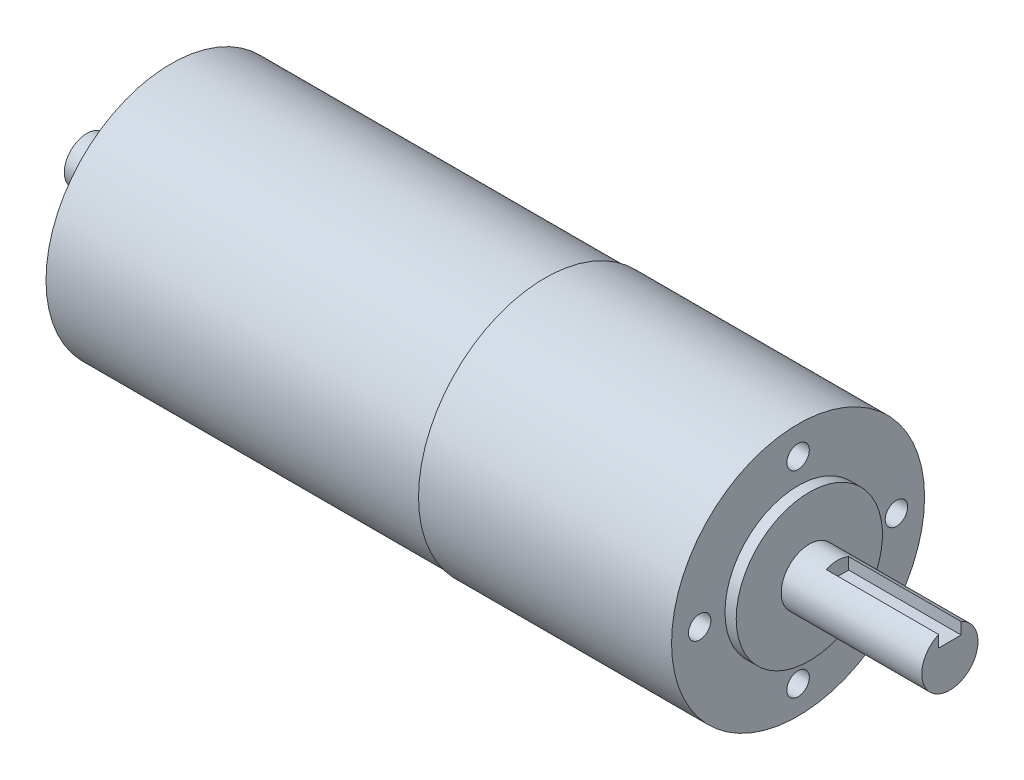
SolidWorks part; units mm, degrees
ref_plane "Front Plane" through (0, 0, 0) normal (0, 0, 1) x (1, 0, 0)
ref_plane "Top Plane" through (0, 0, 0) normal (0, 1, 0) x (1, 0, 0)
ref_plane "Right Plane" through (0, 0, 0) normal (1, 0, 0) x (0, 0, -1)
sketch "Sketch1" plane through (0, 0, 0) normal (1, 0, 0) x (0, 0, -1)
  circle A0 centre (0, 0) radius 5
  dimension "D1" = 10
extrude "Boss-Extrude1" add sketch "Sketch1" against normal blind 25
sketch "Sketch2" plane through (-25, 0, 0) normal (-1, 0, 0) x (0, 0, 1)
  circle A0 centre (0, 0) radius 13
  dimension "D1" = 26
extrude "Boss-Extrude2" add sketch "Sketch2" along normal blind 2
sketch "Sketch3" plane through (-27, 0, 0) normal (-1, 0, 0) x (0, 0, 1)
  circle A0 centre (0, 0) radius 22.5
  dimension "D1" = 45
extrude "Boss-Extrude3" add sketch "Sketch3" along normal blind 45
sketch "Sketch4" plane through (-72, 0, 0) normal (-1, 0, 0) x (0, 0, 1)
  circle A0 centre (0, 0) radius 22.25
  dimension "D1" = 44.5
extrude "Boss-Extrude4" add sketch "Sketch4" along normal blind 66.5
sketch "Sketch5" plane through (-138.5, 0, 0) normal (-1, 0, 0) x (0, 0, 1)
  circle A0 centre (0, 0) radius 10
  dimension "D1" = 20
extrude "Boss-Extrude5" add sketch "Sketch5" along normal blind 5
sketch "Sketch6" plane through (-143.5, 0, 0) normal (-1, 0, 0) x (0, 0, 1)
  circle A0 centre (0, 0) radius 4
  dimension "D1" = 8
extrude "Boss-Extrude6" add sketch "Sketch6" along normal blind 10
sketch "Sketch7" plane through (-27, 0, 0) normal (1, 0, 0) x (0, 0, -1)
  circle A0 centre (0, 17.5) radius 2
  circle A1 centre (0, 0) radius 17.5 construction
  circle A2 centre (17.5, 0) radius 2
  circle A3 centre (0, -17.5) radius 2
  circle A4 centre (-17.5, 0) radius 2
  dimension "D1" = 35
  dimension "D2" = 4
  dimension "D3" = 4
extrude "Cut-Extrude1" cut sketch "Sketch7" against normal blind 9
sketch "Sketch8" plane through (0, 0, 0) normal (1, 0, 0) x (0, 0, -1)
  line L1 (-2, 5) -> (2, 5)
  line L2 (-2, 5) -> (-2, 2.5)
  line L3 (-2, 2.5) -> (2, 2.5)
  line L4 (2, 5) -> (2, 2.5)
  line L5 (-2, 5) -> (2, 2.5) construction
  line L6 (-2, 2.5) -> (2, 5) construction
  circle A1 centre (0, 0) radius 5 construction
  point P0 (0, 3.75)
  dimension "D1" = 2.5
  dimension "D2" = 4
extrude "Cut-Extrude2" cut sketch "Sketch8" against normal blind 20
